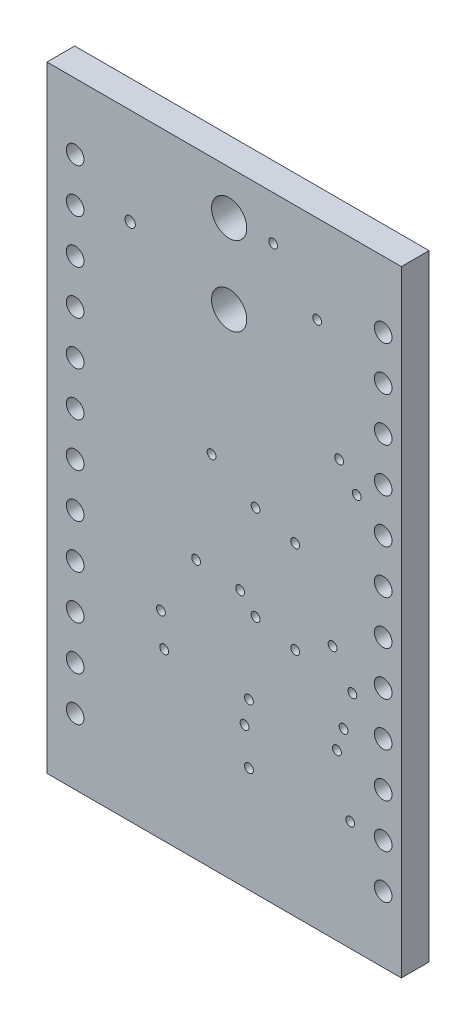
SolidWorks part; units mm, degrees
ref_plane "Front Plane" through (0, 0, 0) normal (0, 0, 1) x (1, 0, 0)
ref_plane "Top Plane" through (0, 0, 0) normal (0, 1, 0) x (1, 0, 0)
ref_plane "Right Plane" through (0, 0, 0) normal (1, 0, 0) x (0, 0, -1)
ref_plane "Dielectric_Layer Layer 1" through (0, 0, 1.6) normal (0, 0, 1) x (1, 0, 0)
sketch "Sketch1" plane through (0, 0, 0) normal (0, 0, 1) x (1, 0, 0)
  line L0 (2.54, 35.56) -> (38.1, 35.56)
  line L1 (38.1, 35.56) -> (38.7574, 35.4735)
  line L2 (38.7574, 35.4735) -> (39.37, 35.2197)
  line L3 (39.37, 35.2197) -> (39.8961, 34.8161)
  line L4 (39.8961, 34.8161) -> (40.2997, 34.29)
  line L5 (40.2997, 34.29) -> (40.5535, 33.6774)
  line L6 (40.5535, 33.6774) -> (40.64, 33.02)
  line L7 (40.64, 33.02) -> (40.64, 2.54)
  line L8 (40.64, 2.54) -> (40.5535, 1.8826)
  line L9 (40.5535, 1.8826) -> (40.2997, 1.27)
  line L10 (40.2997, 1.27) -> (39.8961, 0.7439)
  line L11 (39.8961, 0.7439) -> (39.37, 0.3403)
  line L12 (39.37, 0.3403) -> (38.7574, 0.0865)
  line L13 (38.7574, 0.0865) -> (38.1, 0)
  line L14 (38.1, 0) -> (2.54, 0)
  line L15 (2.54, 0) -> (1.8826, 0.0865)
  line L16 (1.8826, 0.0865) -> (1.27, 0.3403)
  line L17 (1.27, 0.3403) -> (0.7439, 0.7439)
  line L18 (0.7439, 0.7439) -> (0.3403, 1.27)
  line L19 (0.3403, 1.27) -> (0.0865, 1.8826)
  line L20 (0.0865, 1.8826) -> (0, 2.54)
  line L21 (0, 2.54) -> (0, 33.02)
  line L22 (0, 33.02) -> (0.0865, 33.6774)
  line L23 (0.0865, 33.6774) -> (0.3403, 34.29)
  line L24 (0.3403, 34.29) -> (0.7439, 34.8161)
  line L25 (0.7439, 34.8161) -> (1.27, 35.2197)
  line L26 (1.27, 35.2197) -> (1.8826, 35.4735)
  line L27 (1.8826, 35.4735) -> (2.54, 35.56)
extrude "Board_Outline" add sketch "Sketch1" along normal blind 1.6 separate body
sketch "Sketch2" plane through (0, 0, 0) normal (0, 0, 1) x (1, 0, 0)
  circle A0 centre (20.32, 33.02) radius 1.016
  circle A1 centre (20.32, 28.448) radius 1.016
  circle A2 centre (2.54, 33.02) radius 1.651
  circle A3 centre (38.1, 33.02) radius 1.651
  circle A4 centre (2.54, 2.54) radius 1.651
  circle A5 centre (38.1, 2.54) radius 1.651
  circle A6 centre (21.463, 9.525) radius 0.254
  circle A7 centre (27.686, 22.86) radius 0.254
  circle A8 centre (20.955, 14.732) radius 0.254
  circle A9 centre (24.13, 13.335) radius 0.254
  circle A10 centre (24.13, 18.669) radius 0.254
  circle A11 centre (19.304, 20.701) radius 0.254
  circle A12 centre (18.415, 14.986) radius 0.254
  circle A13 centre (16.383, 11.43) radius 0.254
  circle A14 centre (16.571, 9.591) radius 0.254
  circle A15 centre (26.67, 24.13) radius 0.254
  circle A16 centre (26.543, 9.525) radius 0.254
  circle A17 centre (26.924, 10.795) radius 0.254
  circle A18 centre (26.289, 14.605) radius 0.254
  circle A19 centre (21.463, 6.096) radius 0.254
  circle A20 centre (14.605, 29.972) radius 0.3
  circle A21 centre (21.209, 8.128) radius 0.254
  circle A22 centre (27.305, 6.35) radius 0.254
  circle A23 centre (27.432, 12.827) radius 0.254
  circle A24 centre (21.844, 19.304) radius 0.254
  circle A25 centre (21.844, 13.843) radius 0.254
  circle A26 centre (25.4, 30.48) radius 0.254
  circle A27 centre (22.86, 33.02) radius 0.254
extrude "NPTH" cut sketch "Sketch2" along normal through all
sketch "Sketch3" plane through (0, 0, 0) normal (0, 0, 1) x (1, 0, 0)
  circle A0 centre (11.43, 31.75) radius 0.51
  circle A1 centre (11.43, 29.21) radius 0.51
  circle A2 centre (11.43, 26.67) radius 0.51
  circle A3 centre (34.29, 31.75) radius 0.51
  circle A4 centre (11.43, 24.13) radius 0.51
  circle A5 centre (11.43, 21.59) radius 0.51
  circle A6 centre (11.43, 19.05) radius 0.51
  circle A7 centre (11.43, 16.51) radius 0.51
  circle A8 centre (11.43, 13.97) radius 0.51
  circle A9 centre (11.43, 11.43) radius 0.51
  circle A10 centre (11.43, 8.89) radius 0.51
  circle A11 centre (11.43, 6.35) radius 0.51
  circle A12 centre (11.43, 3.81) radius 0.51
  circle A13 centre (29.21, 3.81) radius 0.51
  circle A14 centre (29.21, 6.35) radius 0.51
  circle A15 centre (29.21, 8.89) radius 0.51
  circle A16 centre (29.21, 11.43) radius 0.51
  circle A17 centre (29.21, 13.97) radius 0.51
  circle A18 centre (29.21, 16.51) radius 0.51
  circle A19 centre (29.21, 19.05) radius 0.51
  circle A20 centre (29.21, 21.59) radius 0.51
  circle A21 centre (29.21, 24.13) radius 0.51
  circle A22 centre (29.21, 26.67) radius 0.51
  circle A23 centre (29.21, 29.21) radius 0.51
  circle A24 centre (29.21, 31.75) radius 0.51
  circle A25 centre (6.35, 3.81) radius 0.51
  circle A26 centre (6.35, 6.35) radius 0.51
  circle A27 centre (6.35, 8.89) radius 0.51
  circle A28 centre (6.35, 11.43) radius 0.51
  circle A29 centre (6.35, 13.97) radius 0.51
  circle A30 centre (6.35, 16.51) radius 0.51
  circle A31 centre (34.29, 3.81) radius 0.51
  circle A32 centre (34.29, 6.35) radius 0.51
  circle A33 centre (34.29, 8.89) radius 0.51
  circle A34 centre (34.29, 11.43) radius 0.51
  circle A35 centre (34.29, 13.97) radius 0.51
  circle A36 centre (34.29, 16.51) radius 0.51
  circle A37 centre (34.29, 19.05) radius 0.51
  circle A38 centre (34.29, 21.59) radius 0.51
  circle A39 centre (6.35, 19.05) radius 0.51
  circle A40 centre (6.35, 29.21) radius 0.51
  circle A41 centre (34.29, 24.13) radius 0.51
  circle A42 centre (34.29, 29.21) radius 0.51
  circle A43 centre (6.35, 24.13) radius 0.51
  circle A44 centre (6.35, 26.67) radius 0.51
  circle A45 centre (34.29, 26.67) radius 0.51
  circle A46 centre (6.35, 31.75) radius 0.51
  circle A47 centre (6.35, 21.59) radius 0.51
extrude "PTH" cut sketch "Sketch3" along normal through all
sketch "Sketch4" plane through (0, 0, 1.6) normal (0, 0, 1) x (1, 0, 0)
  line L0 (38.1, 35.56) -> (2.54, 35.56) construction
  line L1 (9.8037, 35.56) -> (-1.8709, 35.56)
  line L2 (9.8037, 35.56) -> (9.8037, -1.7053)
  line L3 (9.8037, -1.7053) -> (-1.8709, -1.7053)
  line L4 (-1.8709, 35.56) -> (-1.8709, -1.7053)
extrude "Cut-Extrude1" cut sketch "Sketch4" against normal blind 10
ref_plane "Plane1" through (38.1, 35.56, 0) normal (-1, 0, 0) x (0, 0, 1)
sketch "Sketch5" plane through (38.1, 35.56, 0) normal (-1, 0, 0) x (0, 0, 1)
  line L1 (42.9372, 2.0921) -> (42.7955, 2.0921)
  line L2 (42.9372, 2.0921) -> (42.9372, 1.9518)
  line L3 (42.9372, 1.9518) -> (42.7955, 1.9518)
  line L4 (42.7955, 2.0921) -> (42.7955, 1.9518)
sketch "Sketch6" plane through (0, 0, 0) normal (0, 0, -1) x (-1, 0, 0)
  line L0 (-9.8037, 0) -> (-38.1, 0) construction
  line L1 (-30.258, 0) -> (-42.8208, 0)
  line L2 (-30.258, 0) -> (-30.258, 36.9348)
  line L3 (-30.258, 36.9348) -> (-42.8208, 36.9348)
  line L4 (-42.8208, 0) -> (-42.8208, 36.9348)
extrude "Cut-Extrude2" cut sketch "Sketch6" against normal blind 10
